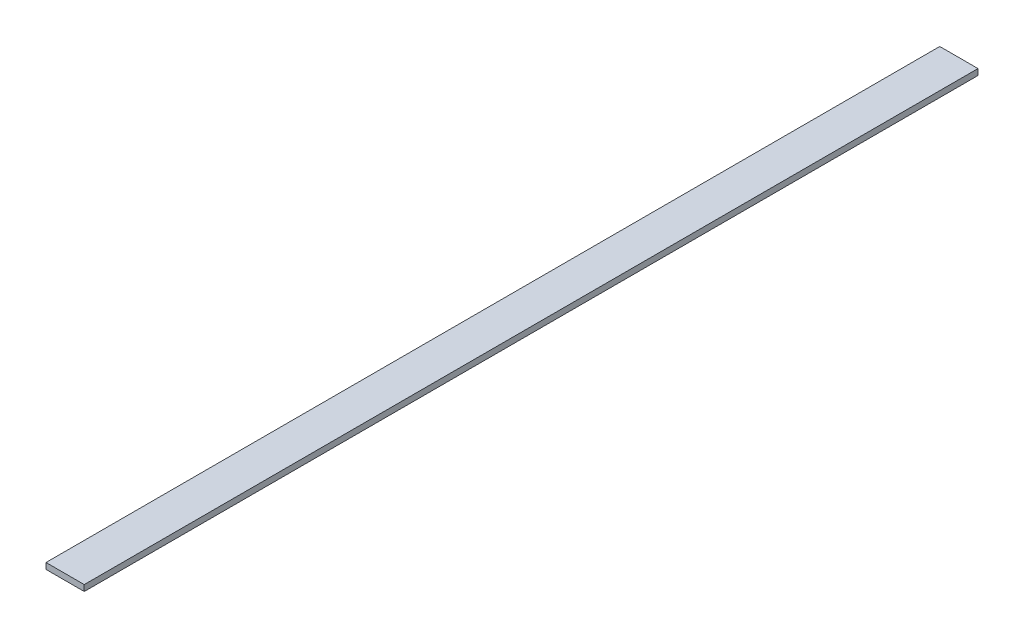
SolidWorks part; units mm, degrees
material "1060 Alloy"
ref_plane "Front Plane" through (0, 0, 0) normal (0, 0, 1) x (1, 0, 0)
ref_plane "Top Plane" through (0, 0, 0) normal (0, 1, 0) x (1, 0, 0)
ref_plane "Right Plane" through (0, 0, 0) normal (1, 0, 0) x (0, 0, -1)
sketch "Sketch1" plane through (0, 0, 0) normal (0, 1, 0) x (1, 0, 0)
  line L1 (-9.5, -222) -> (9.5, -222)
  line L2 (-9.5, -222) -> (-9.5, 222)
  line L3 (-9.5, 222) -> (9.5, 222)
  line L4 (9.5, -222) -> (9.5, 222)
  line L5 (-9.5, -222) -> (9.5, 222) construction
  line L6 (-9.5, 222) -> (9.5, -222) construction
  point P0 (0, 0)
  dimension "D1" = 19
  dimension "D2" = 444
extrude "Boss-Extrude1" add sketch "Sketch1" along normal blind 3
